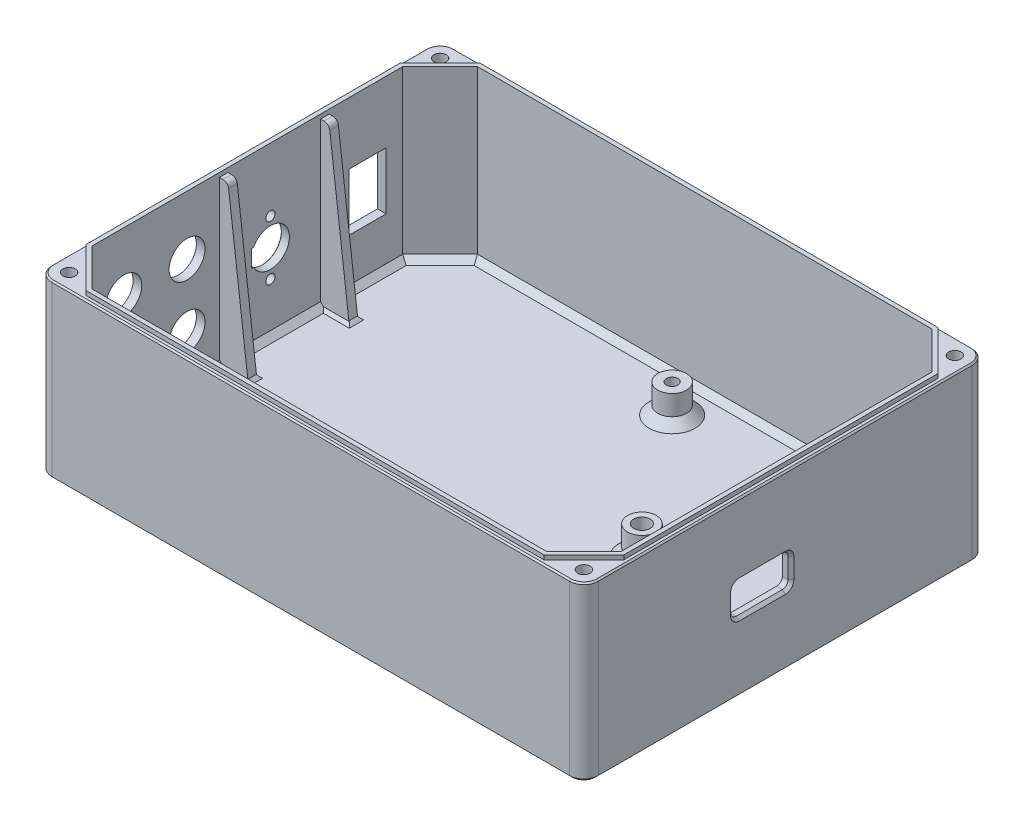
SolidWorks part; units mm, degrees
ref_plane "Front Plane" through (0, 0, 0) normal (0, 0, 1) x (1, 0, 0)
ref_plane "Top Plane" through (0, 0, 0) normal (0, 1, 0) x (1, 0, 0)
ref_plane "Right Plane" through (0, 0, 0) normal (1, 0, 0) x (0, 0, -1)
sketch "Sketch2" plane through (0, 0, 0) normal (0, 1, 0) x (1, 0, 0)
  line L1 (-95, 70) -> (95, 70)
  line L2 (-95, 70) -> (-95, -70)
  line L3 (-95, -70) -> (95, -70)
  line L4 (95, 70) -> (95, -70)
  line L5 (-95, 70) -> (95, -70) construction
  line L6 (-95, -70) -> (95, 70) construction
  point P0 (0, 0)
  dimension "D1" = 190
  dimension "D2" = 140
extrude "Enclosure body" add sketch "Sketch2" along normal blind 60
fillet "Fillet1" radius 5 4 edges at (-95, 30, 70) (-95, 30, -70) (95, 30, -70) (95, 30, 70)
shell "Shell1" thickness 3
sketch "Sketch3" plane through (0, 3, 0) normal (0, 1, 0) x (1, 0, 0)
  line L1 (1.2704, 54.4166) -> (76.2704, 54.4166) construction
  line L2 (1.2704, 54.4166) -> (1.2704, -55.5834) construction
  line L3 (1.2704, -55.5834) -> (76.2704, -55.5834) construction
  line L4 (76.2704, 54.4166) -> (76.2704, -55.5834) construction
  line L5 (1.2704, 54.4166) -> (76.2704, -55.5834) construction
  line L6 (1.2704, -55.5834) -> (76.2704, 54.4166) construction
  circle A0 centre (1.2704, 54.4166) radius 5
  circle A1 centre (1.2704, 54.4166) radius 2
  circle A2 centre (76.2704, 54.4166) radius 5
  circle A3 centre (76.2704, 54.4166) radius 2
  circle A4 centre (76.2704, -55.5834) radius 5
  circle A5 centre (76.2704, -55.5834) radius 2
  circle A6 centre (1.2704, -55.5834) radius 5
  circle A7 centre (1.2704, -55.5834) radius 2
  circle A9 centre (38.7704, 6.4166) radius 2.85
  circle A10 centre (38.7704, 6.4166) radius 5
  dimension "D3" = 4
  dimension "D4" = 10
  dimension "D1" = 10
  dimension "D2" = 5.7
  dimension "D5" = 2
  dimension "D6" = 2
extrude "PCB Supports" add sketch "Sketch3" along normal blind 10
sketch "Sketch6" plane through (0, 3, 0) normal (0, 1, 0) x (1, 0, 0)
  line L0 (-79, 67) -> (-92, 54)
  line L1 (-92, -54) -> (-79, -67)
  line L2 (79, -67) -> (92, -54)
  line L3 (79, 67) -> (92, 54)
  line L4 (-90, -67) -> (90, -67)
  line L5 (92, -65) -> (92, 65)
  line L6 (90, 67) -> (-90, 67)
  line L7 (-90, -67) -> (-79, -67)
  line L9 (92, -65) -> (92, -54)
  line L10 (90, 67) -> (79, 67)
  line L12 (-79, 67) -> (-90, 67)
  line L15 (92, 54) -> (92, 65)
  line L16 (-92, 65) -> (-92, -65) construction
  line L17 (-90, -67) -> (90, -67) construction
  line L18 (92, -65) -> (92, 65) construction
  line L19 (-92, -54) -> (-92, -65)
  line L20 (79, -67) -> (90, -67)
  line L21 (-92, 65) -> (-92, -65)
  line L22 (-92, 65) -> (-92, 54)
  line L26 (90, 67) -> (-90, 67) construction
  arc A4 (90, -67) -> (92, -65) centre (90, -65) ccw
  arc A5 (92, 65) -> (90, 67) centre (90, 65) ccw
  arc A6 (-90, 67) -> (-92, 65) centre (-90, 65) ccw
  arc A7 (-90, 67) -> (-92, 65) centre (-90, 65) ccw
  arc A8 (90, -67) -> (92, -65) centre (90, -65) ccw
  arc A9 (92, 65) -> (90, 67) centre (90, 65) ccw
  arc A12 (-92, -65) -> (-90, -67) centre (-90, -65) ccw
  arc A13 (-92, -65) -> (-90, -67) centre (-90, -65) ccw
  dimension "D3" = 13
  dimension "D4" = 13
  dimension "D5" = 13
  dimension "D6" = 13
  dimension "D7" = 13
  dimension "D8" = 13
  dimension "D9" = 13
  dimension "D1" = 0
extrude "Enclosure corner flanges" add sketch "Sketch6" along normal up to vertex (57 mm away)
sketch "Sketch8" plane through (0, 0, 0) normal (0, -1, 0) x (1, 0, 0)
  line L0 (-85.5, 60.5) -> (-93.5355, 68.5355) construction
  line L1 (-92, -54) -> (-79, -67) construction
  line L2 (85.5, 60.5) -> (93.5355, 68.5355) construction
  line L3 (79, -67) -> (92, -54) construction
  line L4 (-93.5355, -68.5355) -> (-85.5, -60.5) construction
  line L5 (92, 54) -> (79, 67) construction
  line L6 (93.5355, -68.5355) -> (85.5, -60.5) construction
  line L7 (-79, 67) -> (-92, 54) construction
  arc A0 (-90, 70) -> (-95, 65) centre (-90, 65) ccw construction
  arc A1 (95, 65) -> (90, 70) centre (90, 65) ccw construction
  arc A2 (-95, -65) -> (-90, -70) centre (-90, -65) ccw construction
  arc A3 (90, -70) -> (95, -65) centre (90, -65) ccw construction
  circle A4 centre (89.5178, -64.5178) radius 3.8
  circle A5 centre (89.5178, 64.5178) radius 3.8
  circle A6 centre (-89.5178, 64.5178) radius 3.8
  circle A7 centre (-89.5178, -64.5178) radius 3.8
  dimension "D1" = 7.6
  dimension "D2" = 7.6
  dimension "D3" = 7.6
  dimension "D4" = 7.6
extrude "Cut-Extrude1" cut sketch "Sketch8" against normal offset from surface (45.5 mm away) 14.5 up to face at (0, 60, 0)
sketch "Sketch9" plane through (0, 45.5, 0) normal (0, -1, 0) x (1, 0, 0)
  circle A0 centre (-89.5178, 64.5178) radius 2.15
  circle A1 centre (89.5178, 64.5178) radius 2.15
  circle A2 centre (89.5178, -64.5178) radius 2.15
  circle A3 centre (-89.5178, -64.5178) radius 2.15
  circle A4 centre (-89.5178, 64.5178) radius 3.8 construction
  circle A5 centre (-89.5178, -64.5178) radius 3.8 construction
  circle A6 centre (89.5178, -64.5178) radius 3.8 construction
  circle A7 centre (89.5178, 64.5178) radius 3.8 construction
  dimension "D1" = 4.3
  dimension "D2" = 4.3
  dimension "D3" = 4.3
  dimension "D4" = 4.3
extrude "Cut-Extrude2" cut sketch "Sketch9" against normal through all
chamfer "Chamfer1" distance 2 angle 45 8 edges at (-85.5, 3, 60.5) (-92, 3, 0) (-85.5, 3, -60.5) (0, 3, -67) (85.5, 3, -60.5) (0, 3, 67) (85.5, 3, 60.5) (92, 3, 0)
sketch "Sketch10" plane through (95, 0, -30) normal (-1, 0, 0) x (0, 0, 1)
  line L1 (29.9831, 35) -> (45.9831, 35)
  line L2 (27.9831, 33) -> (27.9831, 26)
  line L3 (29.9831, 24) -> (45.9831, 24)
  line L4 (47.9831, 33) -> (47.9831, 26)
  line L5 (27.9831, 35) -> (47.9831, 24) construction
  line L6 (27.9831, 24) -> (47.9831, 35) construction
  line L7 (-35, 0) -> (95, 0) construction
  arc A0 (45.9831, 35) -> (47.9831, 33) centre (45.9831, 33) cw
  arc A1 (45.9831, 24) -> (47.9831, 26) centre (45.9831, 26) ccw
  arc A2 (27.9831, 26) -> (29.9831, 24) centre (29.9831, 26) ccw
  arc A3 (29.9831, 35) -> (27.9831, 33) centre (29.9831, 33) ccw
  point P0 (37.9831, 29.5)
  dimension "D1" = 2
  dimension "D2" = 29.5
  dimension "D3" = 11
  dimension "D4" = 20
extrude "USB cutout" cut sketch "Sketch10" along normal blind 6
sketch "Sketch11" plane through (-95, 0, 0) normal (-1, 0, 0) x (0, 0, 1)
  line L0 (-64.7737, 30) -> (65, 30) construction
  line L1 (-2.1212, 33) -> (-1.4, 33)
  line L2 (-48.2237, 39.95) -> (-35.3237, 39.95)
  line L3 (-8, 20.5) -> (-8, 39.5) construction
  line L8 (-48.2237, 39.95) -> (-48.2237, 20.05)
  line L9 (21, 41) -> (43, 41) construction
  line L10 (-1.4, 33) -> (-1.4, 27)
  line L11 (21, 41) -> (21, 19) construction
  line L12 (21, 19) -> (43, 19) construction
  line L13 (43, 41) -> (43, 19) construction
  line L14 (21, 41) -> (43, 19) construction
  line L15 (21, 19) -> (43, 41) construction
  line L16 (-65, 0) -> (65, 0) construction
  line L17 (-48.2237, 20.05) -> (-35.3237, 20.05)
  line L18 (-35.3237, 39.95) -> (-35.3237, 20.05)
  line L19 (-48.2237, 39.95) -> (-35.3237, 20.05) construction
  line L20 (-48.2237, 20.05) -> (-35.3237, 39.95) construction
  line L21 (-2.1212, 27) -> (-1.4, 27)
  line L22 (-65, 60) -> (-65, 0) construction
  arc A1 (-2.1212, 33) -> (-2.1212, 27) centre (-8, 30) ccw
  circle A7 centre (-8, 39.5) radius 1.6
  circle A8 centre (-8, 20.5) radius 1.6
  circle A10 centre (21, 41) radius 6.25
  circle A11 centre (21, 19) radius 6.25
  circle A12 centre (43, 19) radius 6.25
  circle A13 centre (43, 41) radius 6.25
  circle A14 centre (43, 41) radius 7.5 construction
  point P2 (-41.7737, 30)
  point P10 (32, 30)
  dimension "D4" = 19.9
  dimension "D5" = 13.2
  dimension "D8" = 3.2
  dimension "D9" = 3.2
  dimension "D12" = 12.5
  dimension "D13" = 12.5
  dimension "D14" = 3
  dimension "D15" = 12.5
  dimension "D16" = 12.5
  dimension "D18" = 15
  dimension "D19" = 3
  dimension "D2" = 22
  dimension "D3" = 22
  dimension "D6" = 19
  dimension "D7" = 30
  dimension "D10" = 12.9
  dimension "D11" = 9.5
  dimension "D17" = 40
  dimension "D20" = 23
  dimension "D21" = 57
extrude "Button cutouts" cut sketch "Sketch11" against normal blind 6
chamfer "Chamfer3" distance 1 angle 45 8 edges at (0, 0, -70) (-93.5355, 0, -68.5355) (93.5355, 0, -68.5355) (-95, 0, 0) (95, 0, 0) (-93.5355, 0, 68.5355) (93.5355, 0, 68.5355) (0, 0, 70)
sketch "Sketch14" plane through (0, 60, 0) normal (0, 1, 0) x (1, 0, 0)
ref_plane "Plane1" through (0, 0, 0) normal (0, -1, 0) x (-1, 0, 0)
sketch "Sketch15" plane through (-92, 0, 0) normal (1, 0, 0) x (0, 0, -1)
  line L0 (53.1716, 3) -> (-53.1716, 3) construction
  line L1 (-34.0694, 3) -> (-31.0694, 3)
  line L2 (-34.0694, 3) -> (-34.0694, 15.6591)
  line L3 (-34.0694, 15.6591) -> (-31.0694, 15.6591)
  line L4 (-31.0694, 3) -> (-31.0694, 15.6591)
  line L5 (54, 60) -> (-54, 60) construction
  line L6 (25.408, 3) -> (28.408, 3)
  line L7 (25.408, 3) -> (25.408, 60)
  line L8 (25.408, 60) -> (28.408, 60)
  line L9 (28.408, 3) -> (28.408, 60)
  line L10 (-65, 0) -> (65, 0) construction
  line L11 (-53.1716, 3) -> (53.1716, 3) construction
  line L12 (-9.7469, 60) -> (-6.7469, 60)
  line L13 (-9.7469, 60) -> (-9.7469, 3)
  line L14 (-9.7469, 3) -> (-6.7469, 3)
  line L15 (-6.7469, 60) -> (-6.7469, 3)
  dimension "D1" = 15.6591
  dimension "D2" = 3
  dimension "D3" = 3
  dimension "D4" = 3
extrude "Boss-Extrude6" add sketch "Sketch15" along normal blind 10
sketch "Sketch16" plane through (0, 0, 34.0694) normal (0, 0, 1) x (1, 0, 0)
  line L0 (-82, 60) -> (-82, 3)
  line L1 (-82, 3) -> (-89, 60)
  line L2 (-82, 60) -> (-92, 60) construction
  line L3 (-89, 60) -> (-82, 60)
  dimension "D1" = 7
extrude "Cut-Extrude3" cut sketch "Sketch16" against normal up to surface (62.4775 mm away) up to face at (-87.6, 26.2, -28.408)
chamfer "Chamfer4" distance 3 angle 45 5 edges at (76.2704, 3, 60.5834) (1.2704, 3, 60.5834) (76.2704, 3, -49.4166) (38.7704, 3, -1.4166) (1.2704, 3, -49.4166)
fillet "Fillet2" radius 2 3 edges at (-83.5546, 15.6591, 32.5694) (-89, 60, -26.908) (-89, 60, 8.2469)
sketch "Sketch17" plane through (0, 60, 0) normal (0, 1, 0) x (1, 0, 0)
  line L0 (79, 67) -> (92, 54) construction
  line L1 (92, -54) -> (92, 54) construction
  line L2 (92, -54) -> (79, -67) construction
  line L3 (79, -67) -> (-79, -67) construction
  line L4 (-79, -67) -> (-92, -54) construction
  line L5 (79, 67) -> (-79, 67) construction
  line L6 (-92, 54) -> (-79, 67) construction
  line L7 (79, 67) -> (92, 54)
  line L8 (92, -54) -> (92, 54)
  line L9 (92, -54) -> (79, -67)
  line L10 (79, -67) -> (-79, -67)
  line L11 (-79, -67) -> (-92, -54)
  line L12 (79, 67) -> (-79, 67)
  line L13 (-92, 54) -> (-79, 67)
  line L14 (-92, 54) -> (-92, -54)
  line L15 (-93.5, 54.6213) -> (-93.5, -54.6213)
  line L16 (-79.6213, -68.5) -> (-93.5, -54.6213)
  line L17 (79.6213, -68.5) -> (-79.6213, -68.5)
  line L18 (93.5, -54.6213) -> (79.6213, -68.5)
  line L19 (93.5, -54.6213) -> (93.5, 54.6213)
  line L20 (79.6213, 68.5) -> (93.5, 54.6213)
  line L21 (79.6213, 68.5) -> (-79.6213, 68.5)
  line L22 (-93.5, 54.6213) -> (-79.6213, 68.5)
  dimension "D1" = 1.5
extrude "Boss-Extrude7" add sketch "Sketch17" along normal blind 1.5
chamfer "Chamfer5" distance 1 angle 45 9 edges at (-86, 3, -28.408) (-82, 3, -26.908) (-86, 3, -25.408) (-86, 3, 9.7469) (-86, 3, 6.7469) (-82, 3, 8.2469) (-86, 3, 31.0694) (-82, 3, 32.5694) (-86, 3, 34.0694)
chamfer "Chamfer6" distance 1 angle 45 8 edges at (95, 29.5, 17.9831) (95, 34.4142, 17.3973) (95, 24.5858, 17.3973) (95, 35, 7.9831) (95, 24, 7.9831) (95, 34.4142, -1.4311) (95, 24.5858, -1.4311) (95, 29.5, -2.0169)
chamfer "Chamfer7" distance 0.2 angle 45 1 edges at (-95, 30, -14.6)
chamfer "Chamfer8" distance 0.5 angle 45 8 edges at (0, 60, -70) (-93.5355, 60, -68.5355) (93.5355, 60, -68.5355) (-95, 60, 0) (95, 60, 0) (-93.5355, 60, 68.5355) (93.5355, 60, 68.5355) (0, 60, 70)
